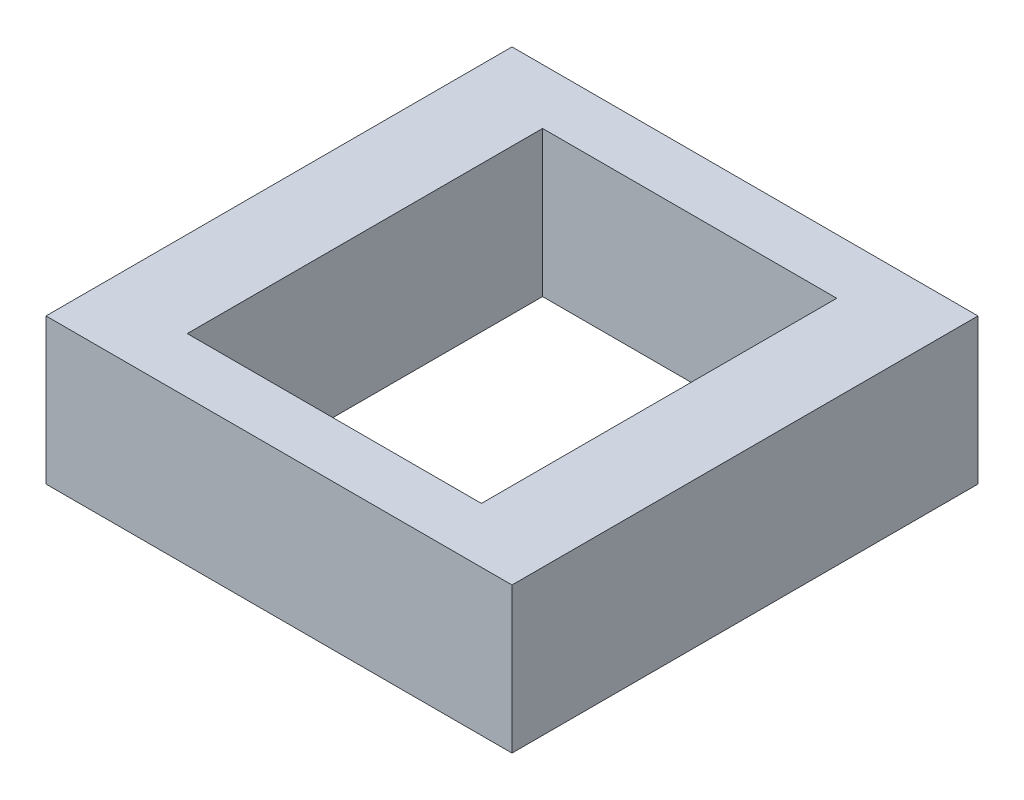
SolidWorks part; units mm, degrees
ref_plane "Front Plane" through (0, 0, 0) normal (0, 0, 1) x (1, 0, 0)
ref_plane "Top Plane" through (0, 0, 0) normal (0, 1, 0) x (1, 0, 0)
ref_plane "Right Plane" through (0, 0, 0) normal (1, 0, 0) x (0, 0, -1)
sketch "Sketch1" plane through (0, 0, 0) normal (0, 1, 0) x (1, 0, 0)
  line L6 (-8, -8) -> (8, -8)
  line L11 (-8, -8) -> (-8, 8)
  line L12 (-8, 8) -> (8, 8)
  line L16 (8, -8) -> (8, 8)
  line L17 (-8, -8) -> (8, 8) construction
  line L18 (-8, 8) -> (8, -8) construction
  line L19 (-5.05, -6.1) -> (5.05, -6.1)
  line L20 (-5.05, -6.1) -> (-5.05, 6.1)
  line L21 (-5.05, 6.1) -> (5.05, 6.1)
  line L22 (5.05, -6.1) -> (5.05, 6.1)
  line L23 (-5.05, -6.1) -> (5.05, 6.1) construction
  line L24 (-5.05, 6.1) -> (5.05, -6.1) construction
  point P0 (0, 0)
  point P6 (0, 0)
  dimension "D1" = 16
  dimension "D2" = 16
  dimension "D3" = 10.1
  dimension "D4" = 12.2
extrude "Boss-Extrude1" add sketch "Sketch1" along normal blind 5
